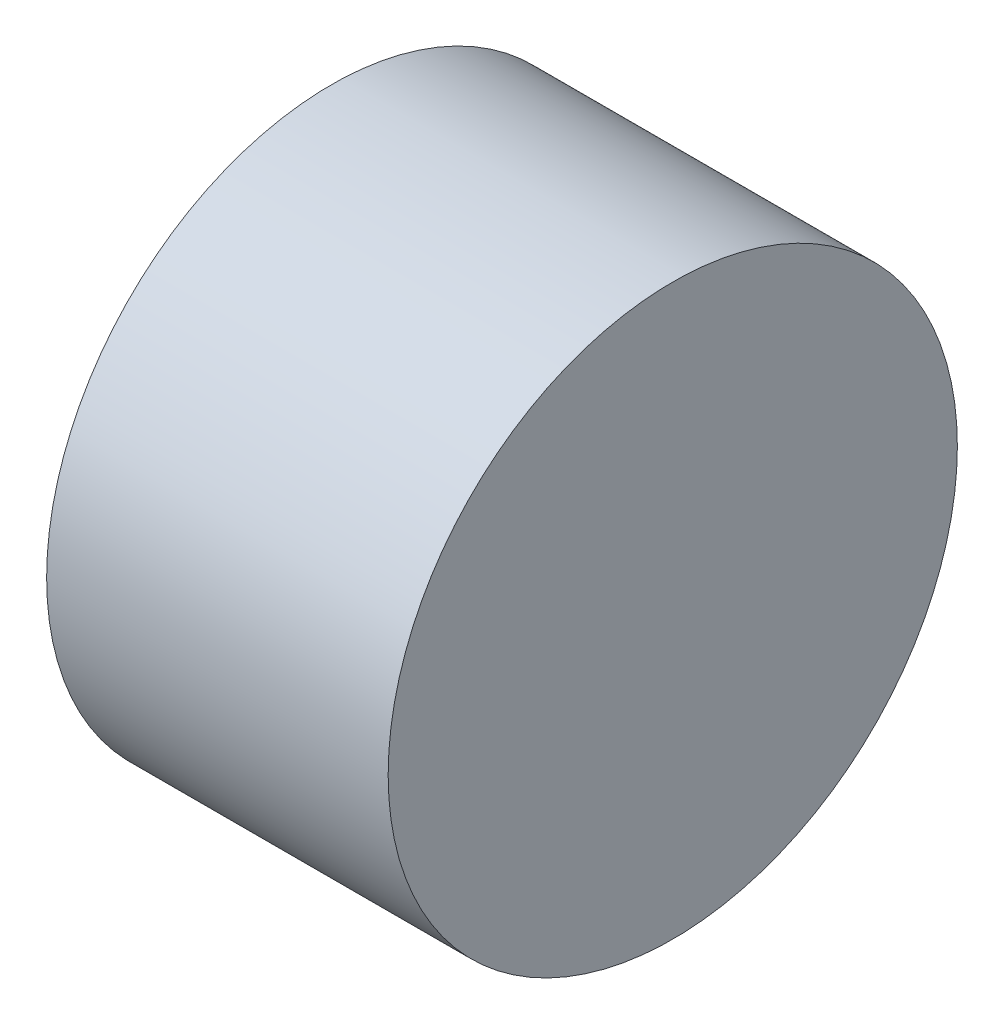
SolidWorks part; units mm, degrees
ref_plane "Front Plane" through (0, 0, 0) normal (0, 0, 1) x (1, 0, 0)
ref_plane "Top Plane" through (0, 0, 0) normal (0, 1, 0) x (1, 0, 0)
ref_plane "Right Plane" through (0, 0, 0) normal (1, 0, 0) x (0, 0, -1)
sketch "Sketch2" plane through (0, 0, 0) normal (1, 0, 0) x (0, 0, -1)
  circle A0 centre (0, 0) radius 1.455
  dimension "D1" = 2.91
extrude "Boss-Extrude3" add sketch "Sketch2" along normal blind 6 contours A0
sketch "Sketch3" plane through (6, 0, 0) normal (1, 0, 0) x (0, 0, -1)
  circle A0 centre (0, 0) radius 2.5
  dimension "D1" = 5
extrude "Boss-Extrude4" add sketch "Sketch3" along normal blind 3
sketch "Sketch4" plane through (0, 0, 0) normal (0, 1, 0) x (1, 0, 0)
  circle A0 centre (3, 0) radius 0.5
  dimension "D1" = 1
  dimension "D2" = 3
extrude "Cut-Extrude1" cut sketch "Sketch4" against normal through all both and the other way through all
ref_plane "Plane1" through (3, 0, 0) normal (-1, 0, 0) x (0, 0, 1)
sketch "Sketch6" plane through (3, 0, 0) normal (-1, 0, 0) x (0, 0, 1)
  circle A0 centre (0, 0) radius 1.575
  dimension "D1" = 3.15
extrude "Boss-Extrude5" add sketch "Sketch6" along normal blind 0.15
sketch "Sketch7" plane through (0, 0, 0) normal (0, 0, 1) x (1, 0, 0)
  line L0 (2.85, 1.825) -> (0, 0.8)
  line L1 (0, 0.8) -> (2.85, 0.8)
  line L2 (2.85, 0.8) -> (2.85, 1.825)
  dimension "D1" = 0
  dimension "D2" = 0
  dimension "D3" = 0.25
  dimension "D4" = 0.8
  dimension "D5" = 0
ref_axis "Axis1" through (9.45, 0, 0) along (-1, 0, 0)
revolve "Revolve1" add sketch "Sketch7" angle 360 about axis through (9.45, 0, 0) along (-1, 0, 0)
sketch "Sketch8" plane through (0, 0, 0) normal (-1, 0, 0) x (0, 0, 1)
  circle A0 centre (0, 0) radius 1.455
  circle A1 centre (0, 0) radius 1.455 construction
  dimension "D1" = 0
extrude "Cut-Extrude2" cut sketch "Sketch8" against normal offset from surface (8 mm away) 1 up to face at (9, 0, -2.5)
sketch "Sketch10" plane through (6, 0, 0) normal (-1, 0, 0) x (0, 0, 1)
  circle A0 centre (0, 0) radius 3.3349
extrude "Cut-Extrude3" cut sketch "Sketch10" along normal through all
sketch "Sketch11" plane through (6, 0, 0) normal (-1, 0, 0) x (0, 0, 1)
  circle A0 centre (0, 0) radius 1.456
  circle A1 centre (0, 0) radius 1.455 construction
  dimension "D1" = 0.001
extrude "Cut-Extrude4" cut sketch "Sketch11" against normal offset from surface (2 mm away) 1 up to face at (9, 0, -2.5)
